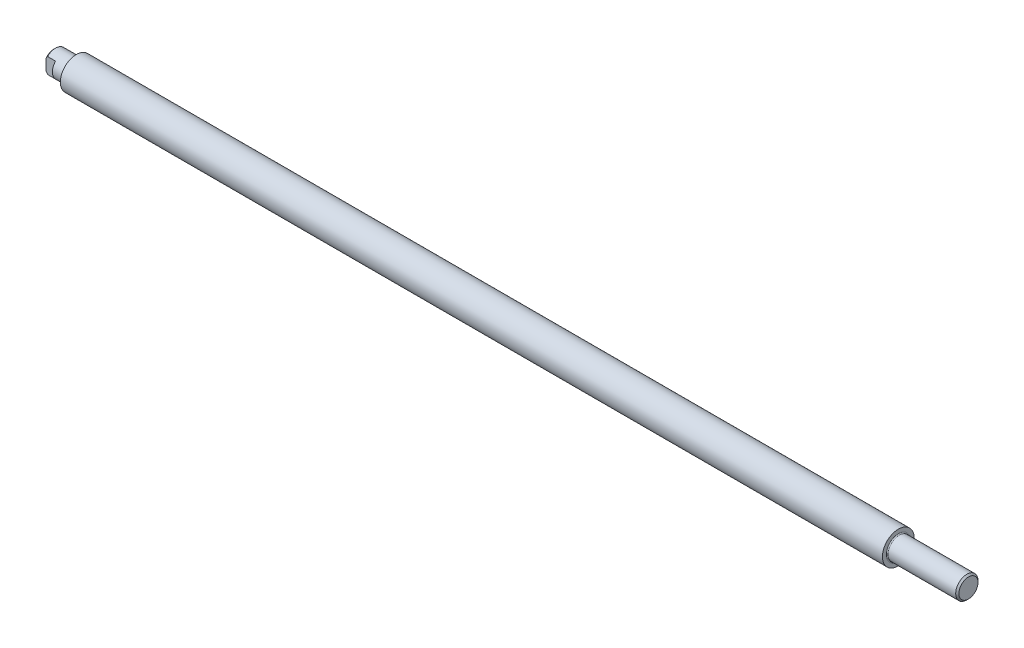
SolidWorks part; units mm, degrees
ref_plane "Front Plane" through (0, 0, 0) normal (0, 0, 1) x (1, 0, 0)
ref_plane "Top Plane" through (0, 0, 0) normal (0, 1, 0) x (1, 0, 0)
ref_plane "Right Plane" through (0, 0, 0) normal (1, 0, 0) x (0, 0, -1)
sketch "Sketch1" plane through (0, 0, 0) normal (0, 0, 1) x (1, 0, 0)
  line L0 (7, 5) -> (7, 0)
  line L1 (7, 0) -> (265, 0)
  line L2 (265, 0) -> (265, 5)
  line L3 (265, 5) -> (7, 5)
  line L4 (7, 0) -> (265, 0) construction
revolve "Revolve1" add sketch "Sketch1" angle 360 about L4
sketch "Sketch2" plane through (7, 0, 0) normal (-1, 0, 0) x (0, 0, 1)
  circle A0 centre (0, 0) radius 3.5
extrude "Boss-Extrude1" add sketch "Sketch2" along normal blind 7
sketch "Sketch3" plane through (0, 0, 0) normal (-1, 0, 0) x (0, 0, 1)
  line L0 (2.5, 2.4495) -> (2.5, -2.4495)
  arc A0 (2.5, -2.4495) -> (2.5, 2.4495) centre (0, 0) ccw
extrude "Cut-Extrude1" cut sketch "Sketch3" against normal blind 3
sketch "Sketch4" plane through (265, 0, 0) normal (1, 0, 0) x (0, 0, -1)
  circle A0 centre (0, 0) radius 3.5
extrude "Boss-Extrude2" add sketch "Sketch4" along normal blind 22
chamfer "Chamfer1" distance 0.5 angle 45 2 edges at (287, 0, -3.5) (0, 0, -3.5)
fillet "Fillet1" radius 0.3 2 edges at (7, 0, 3.5) (265, 0, -3.5)
